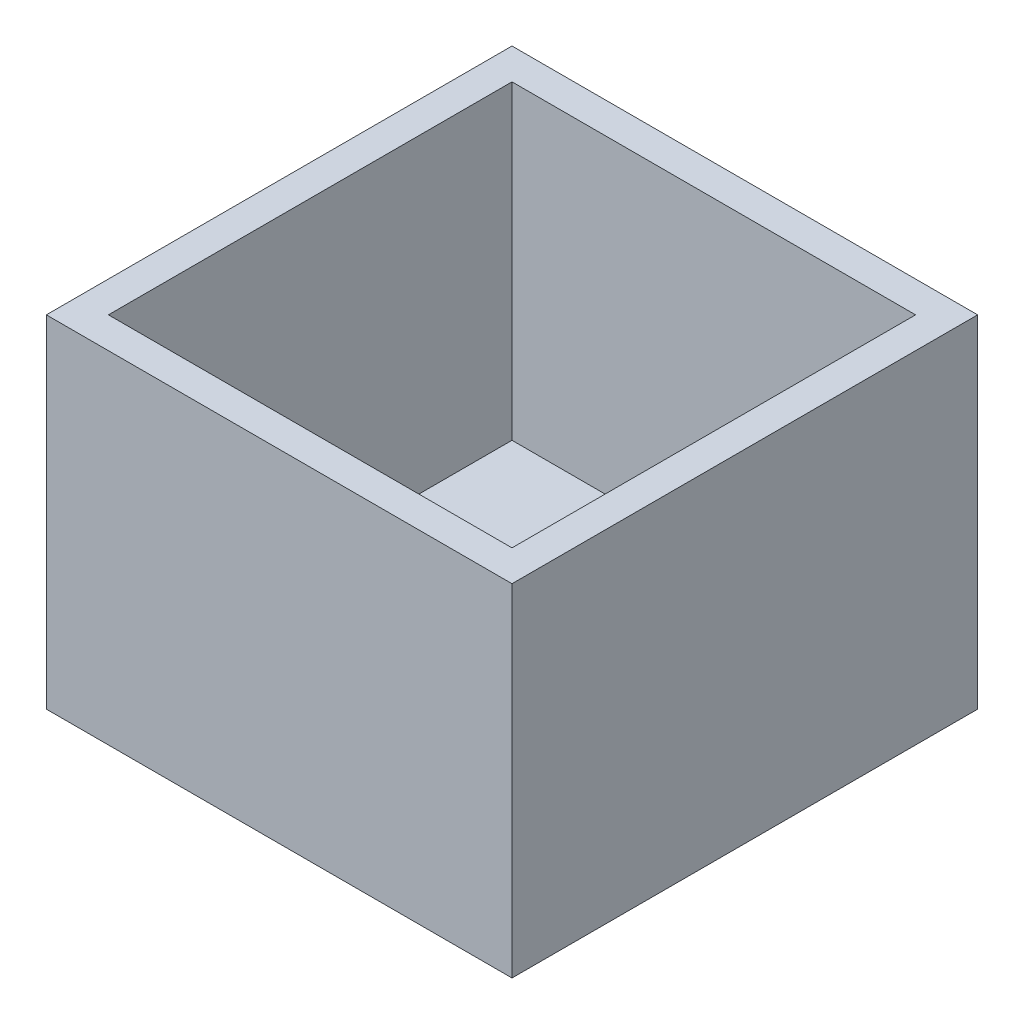
SolidWorks part; units mm, degrees
material "Silicon Dioxide"
ref_plane "Front Plane" through (0, 0, 0) normal (0, 0, 1) x (1, 0, 0)
ref_plane "Top Plane" through (0, 0, 0) normal (0, 1, 0) x (1, 0, 0)
ref_plane "Right Plane" through (0, 0, 0) normal (1, 0, 0) x (0, 0, -1)
sketch "Sketch5" plane through (0, 0, 0) normal (0, 1, 0) x (1, 0, 0)
  line L1 (-6.5, -6.5) -> (6.5, -6.5)
  line L2 (-6.5, -6.5) -> (-6.5, 6.5)
  line L3 (-6.5, 6.5) -> (6.5, 6.5)
  line L4 (6.5, -6.5) -> (6.5, 6.5)
  line L5 (-6.5, -6.5) -> (6.5, 6.5) construction
  line L6 (-6.5, 6.5) -> (6.5, -6.5) construction
  line L7 (-7.5, -7.5) -> (7.5, -7.5)
  line L8 (-7.5, -7.5) -> (-7.5, 7.5)
  line L9 (-7.5, 7.5) -> (7.5, 7.5)
  line L10 (7.5, -7.5) -> (7.5, 7.5)
  line L11 (-7.5, -7.5) -> (7.5, 7.5) construction
  line L12 (-7.5, 7.5) -> (7.5, -7.5) construction
  point P0 (0, 0)
  point P6 (0, 0)
  dimension "D1" = 1
  dimension "D2" = 15
extrude "Boss-Extrude1" add sketch "Sketch5" along normal blind 10
sketch "Sketch6" plane through (0, 0, -7.5) normal (0, 0, -1) x (-1, 0, 0)
  line L1 (-7.5, 0) -> (7.5, 0)
  line L2 (-7.5, 0) -> (-7.5, -1)
  line L3 (-7.5, -1) -> (7.5, -1)
  line L4 (7.5, 0) -> (7.5, -1)
  point P5 (0, 0)
  dimension "D1" = 1
extrude "Boss-Extrude2" add sketch "Sketch6" against normal up to surface (15 mm away) up to face at (0, 5, 7.5)
